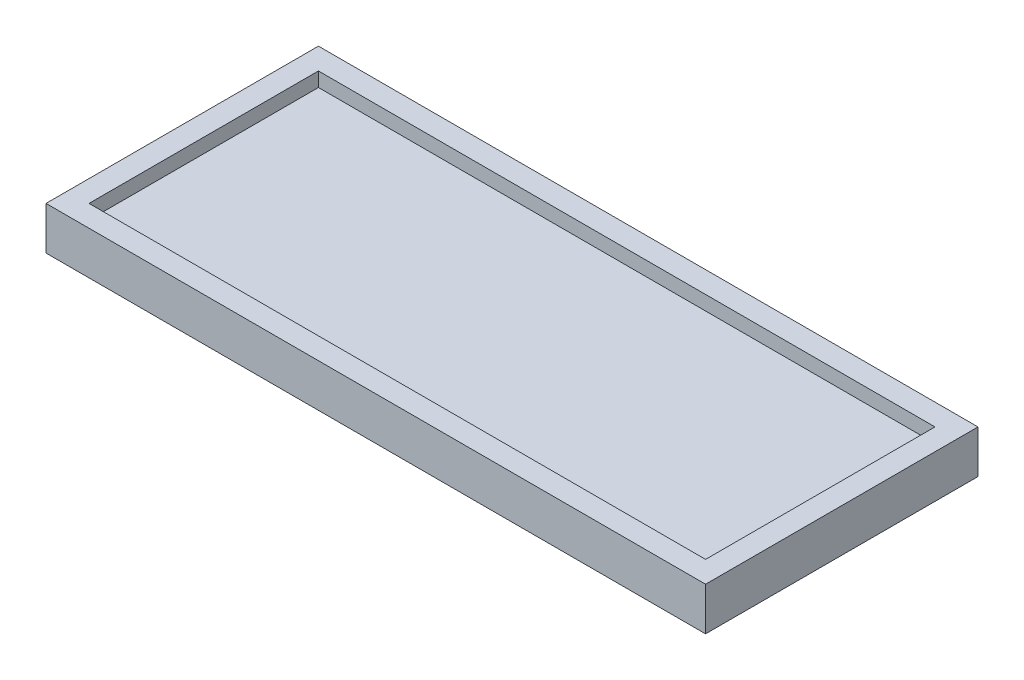
SolidWorks part; units mm, degrees
ref_plane "Front Plane" through (0, 0, 0) normal (0, 0, 1) x (1, 0, 0)
ref_plane "Top Plane" through (0, 0, 0) normal (0, 1, 0) x (1, 0, 0)
ref_plane "Right Plane" through (0, 0, 0) normal (1, 0, 0) x (0, 0, -1)
sketch "Sketch1" plane through (0, 0, 0) normal (0, 1, 0) x (1, 0, 0)
  line L1 (-21.5, 8) -> (21.5, 8)
  line L2 (-21.5, 8) -> (-21.5, -8)
  line L3 (-21.5, -8) -> (21.5, -8)
  line L4 (21.5, 8) -> (21.5, -8)
  line L5 (-21.5, 8) -> (21.5, -8) construction
  line L6 (-21.5, -8) -> (21.5, 8) construction
  point P0 (0, 0)
extrude "Boss-Extrude1" add sketch "Sketch1" along normal blind 2
sketch "Sketch2" plane through (0, 0, 0) normal (0, -1, 0) x (1, 0, 0)
  line L4 (23, -9.5) -> (23, 9.5)
  line L5 (23, 9.5) -> (-23, 9.5)
  line L6 (-23, 9.5) -> (-23, -9.5)
  line L7 (-23, -9.5) -> (23, -9.5)
  line L8 (21.5, -8) -> (21.5, 8)
  line L9 (21.5, 8) -> (-21.5, 8)
  line L10 (-21.5, 8) -> (-21.5, -8)
  line L11 (-21.5, -8) -> (21.5, -8)
  line L12 (21.5, -8) -> (21.5, 8)
  line L13 (21.5, 8) -> (-21.5, 8)
  line L14 (-21.5, 8) -> (-21.5, -8)
  line L15 (-21.5, -8) -> (21.5, -8)
  dimension "D1" = 0
  dimension "D2" = 1.5
extrude "Boss-Extrude4" add sketch "Sketch2" against normal blind 3
